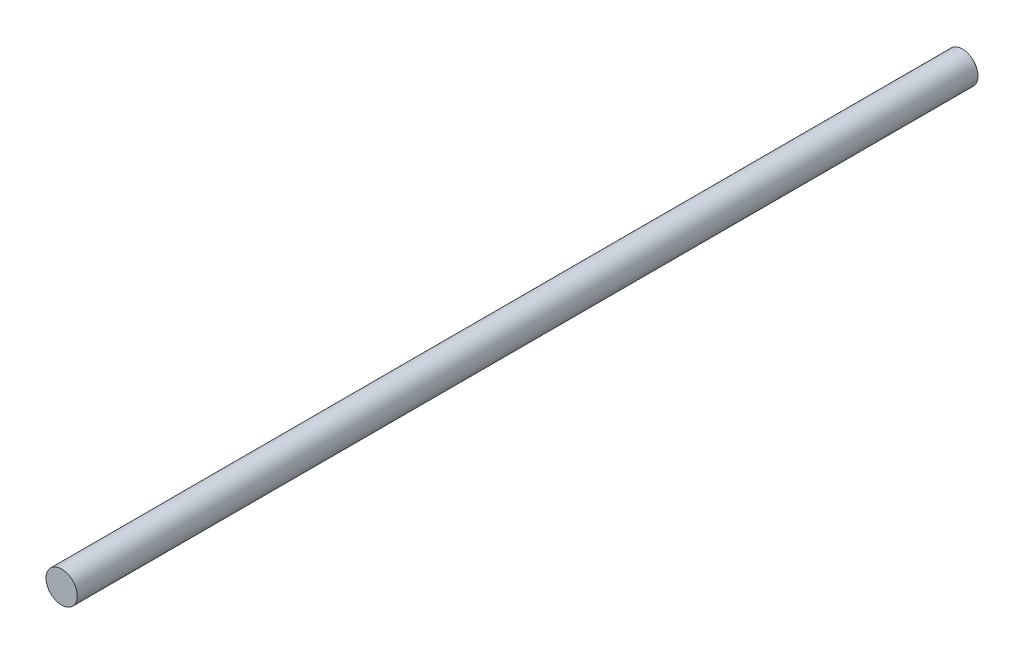
SolidWorks part; units mm, degrees
ref_plane "Front Plane" through (0, 0, 0) normal (0, 0, 1) x (1, 0, 0)
ref_plane "Top Plane" through (0, 0, 0) normal (0, 1, 0) x (1, 0, 0)
ref_plane "Right Plane" through (0, 0, 0) normal (1, 0, 0) x (0, 0, -1)
sketch "Sketch1" plane through (0, 0, 0) normal (0, 0, 1) x (1, 0, 0)
  circle A0 centre (0, 0) radius 12.5
  dimension "D1" = 25
extrude "Boss-Extrude1" add sketch "Sketch1" along normal blind 720
